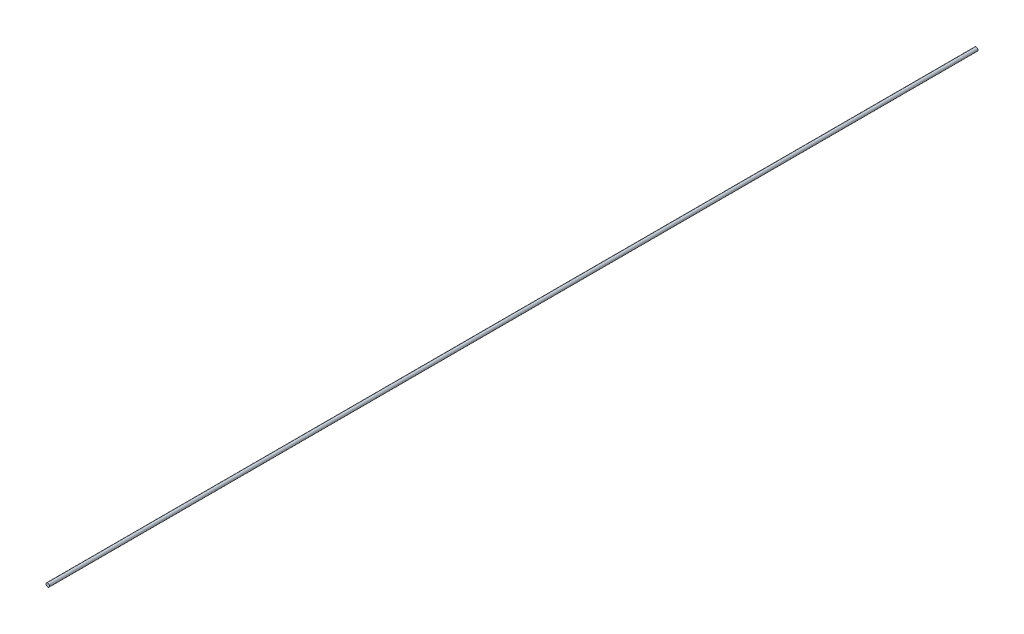
SolidWorks part; units mm, degrees
ref_plane "Front Plane" through (0, 0, 0) normal (0, 0, 1) x (1, 0, 0)
ref_plane "Top Plane" through (0, 0, 0) normal (0, 1, 0) x (1, 0, 0)
ref_plane "Right Plane" through (0, 0, 0) normal (1, 0, 0) x (0, 0, -1)
sketch "Sketch1" plane through (0, 0, 0) normal (0, 0, 1) x (1, 0, 0)
  circle A0 centre (0, 0) radius 2
  dimension "D1" = 4
extrude "Boss-Extrude1" add sketch "Sketch1" along normal blind 1034.05
